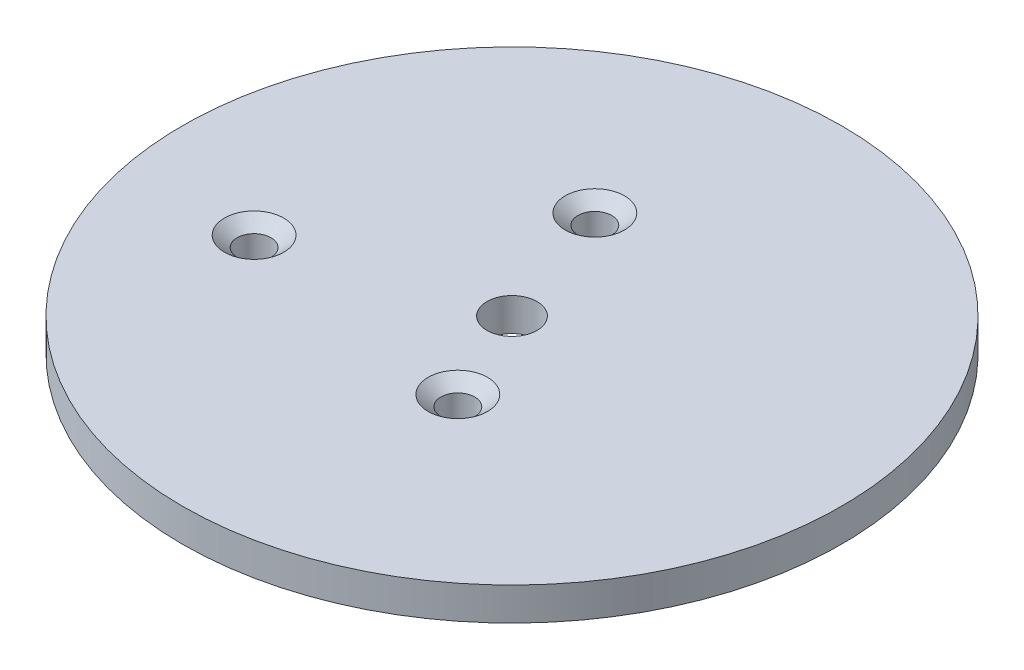
SolidWorks part; units mm, degrees
ref_plane "Front Plane" through (0, 0, 0) normal (0, 0, 1) x (1, 0, 0)
ref_plane "Top Plane" through (0, 0, 0) normal (0, 1, 0) x (1, 0, 0)
ref_plane "Right Plane" through (0, 0, 0) normal (1, 0, 0) x (0, 0, -1)
sketch "Sketch1" plane through (0, 0, 0) normal (0, 1, 0) x (1, 0, 0)
  circle A0 centre (0, 0) radius 31.75
  dimension "D1" = 63.5
extrude "Boss-Extrude1" add sketch "Sketch1" along normal blind 3.175
sketch "Sketch2" plane through (0, 3.175, 0) normal (0, 1, 0) x (1, 0, 0)
  circle A0 centre (0, 0) radius 2.413
  circle A1 centre (0, 0) radius 24.0538 construction
  circle A2 centre (-6.6548, 0) radius 17.399 construction
  circle A4 centre (-19.1658, -5.6802) radius 0.7937
  circle A5 centre (-4.6077, 12.5898) radius 0.7938
  circle A6 centre (3.9355, -9.1528) radius 0.7938
  circle A8 centre (3.9355, -9.1528) radius 1.2437 construction
  circle A10 centre (-19.1658, -5.6802) radius 1.0787 construction
  point P16 (-6.6127, -0.7477)
  dimension "D1" = 4.826
  dimension "D2" = 48.1076
  dimension "D3" = 34.798
  dimension "D5" = 1.5875
  dimension "D7" = 3
extrude "Cut-Extrude1" cut sketch "Sketch2" against normal through all
hole_wizard "CSK for #4 Flat Head Machine Screw (100)1" positions "Sketch4" profile "Sketch3" countersink size "#4" standard "ANSI Inch" end condition through all
sketch "Sketch4" plane through (0, 3.175, 0) normal (0, 1, 0) x (1, 0, 0)
  point P0 (3.9355, -9.1528)
  point P3 (-19.1658, -5.6802)
  point P6 (-4.6077, 12.5898)
sketch "Sketch3" plane through (3.9355, 3.175, 9.1528) normal (1, 0, 0) x (0, 0, 1)
  line L0 (0, 0) -> (0, 3.175)
  line L1 (0, 3.175) -> (1.6319, 3.175)
  line L2 (1.6319, 3.175) -> (1.6319, 1.0284)
  line L3 (1.6319, 1.0284) -> (2.8575, 0)
  line L5 (2.8575, 0) -> (0, 0)
  line L6 (-1.6319, 1.0284) -> (-2.8575, 0) construction
  line L11 (0, -6.35) -> (0, 107.95) construction
  dimension "Thru Hole Dia." = 3.2639
  dimension "Thru Hole Depth" = 3.175
  dimension "Near C'Sink Dia." = 5.715
  dimension "Near C'Sink Angle" = 100
